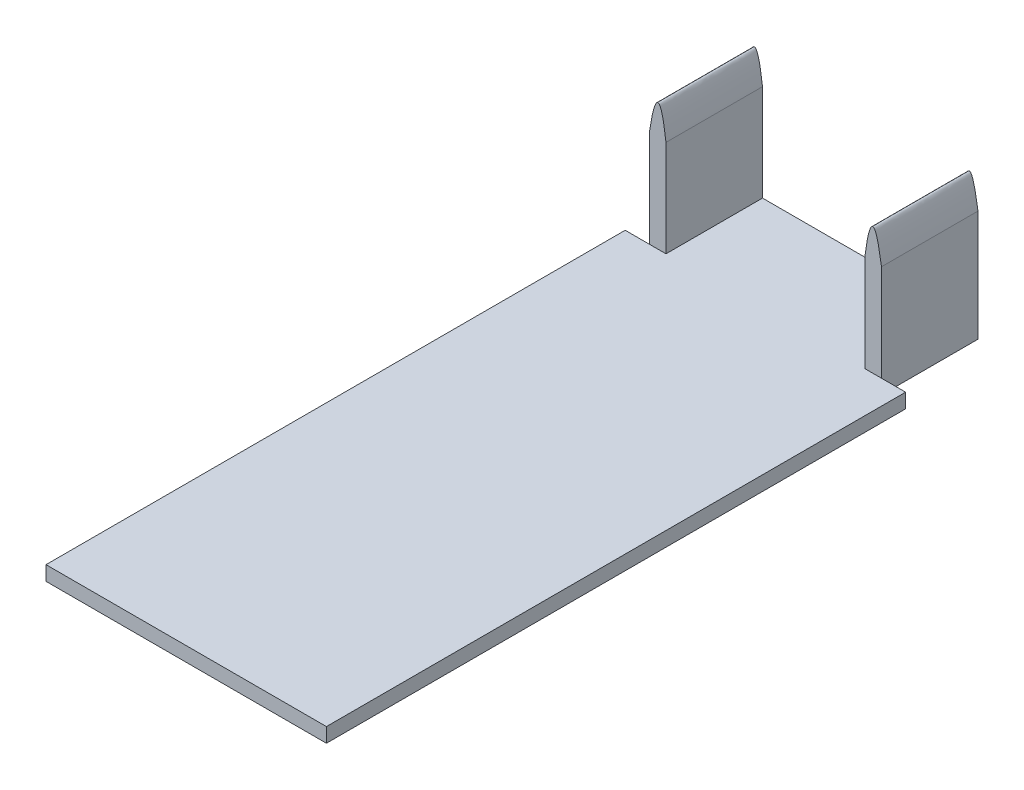
SolidWorks part; units mm, degrees
ref_plane "Front Plane" through (0, 0, 0) normal (0, 0, 1) x (1, 0, 0)
ref_plane "Top Plane" through (0, 0, 0) normal (0, 1, 0) x (1, 0, 0)
ref_plane "Right Plane" through (0, 0, 0) normal (1, 0, 0) x (0, 0, -1)
sketch "Sketch1" plane through (0, 0, 0) normal (0, 0, 1) x (1, 0, 0)
  line L0 (-31.0002, 89.8) -> (31.0002, 89.8) construction
  line L1 (-19.45, 0) -> (-19.45, 22.2)
  line L2 (-19.45, 22.2) -> (19.45, 22.2) construction
  line L3 (19.45, 3) -> (19.45, 22.2)
  line L4 (19.45, 22.2) -> (25.05, 22.2) construction
  line L5 (22.25, 22.2) -> (22.25, 16.6) construction
  line L6 (25.05, 22.2) -> (25.05, 71.1)
  line L7 (29, 72.2) -> (29, -3)
  line L8 (22.25, 16.6) -> (22.25, 71.1) construction
  line L9 (19.6329, 71.1) -> (19.6329, 64.8)
  line L10 (-22.25, 16.6) -> (-22.25, 71.1) construction
  line L11 (-22.25, 22.2) -> (-22.25, 16.6) construction
  line L12 (-19.45, 22.2) -> (-25.05, 22.2) construction
  line L13 (-19.6329, 71.1) -> (-19.5947, 64.8)
  line L14 (-29, 72.2) -> (-29, 0)
  line L15 (-25.05, 22.2) -> (-25.05, 71.1)
  line L16 (-19.45, 0) -> (-19.45, 22.2)
  line L17 (-24.05, 64.8) -> (-24.05, 41.8)
  line L18 (0, 89.8) -> (0, 69.3) construction
  line L19 (25.05, 64.8) -> (33.55, 64.8)
  line L20 (-25.05, 64.8) -> (-33.55, 64.8)
  line L21 (33.55, 64.8) -> (33.55, 61.8)
  line L22 (33.55, 61.8) -> (29, 61.8)
  line L23 (-30.35, 3) -> (29, 3)
  line L24 (-33.55, 0) -> (33.55, 0)
  line L25 (-33.55, 0) -> (-33.55, 11.2)
  line L26 (-33.55, 11.2) -> (-29, 11.2)
  line L27 (33.55, 11.2) -> (29, 11.2)
  line L28 (33.55, 0) -> (33.55, 11.2)
  line L29 (-33.55, 64.8) -> (-33.55, 61.8)
  line L30 (-33.55, 61.8) -> (-29, 61.8)
  line L31 (-24.05, 41.8) -> (24.05, 41.8)
  line L32 (-20.5947, 64.8) -> (-20.5947, 44.8)
  line L33 (-20.5947, 44.8) -> (20.5947, 44.8)
  line L34 (24.05, 64.8) -> (24.05, 41.8)
  line L35 (20.5947, 64.8) -> (20.5947, 44.8)
  arc A0 (-19.45, 22.2) -> (19.45, 22.2) centre (0, 44.8) ccw
  arc A1 (-19.5947, 64.8) -> (19.6329, 64.8) centre (0.0191, 24.3054) cw
  arc A2 (-33.55, 64.8) -> (33.55, 64.8) centre (0, 54.7879) cw
  spline S0 degree 2 poles (19.45, 22.2) (22.25, 11) (25.05, 22.2) knots 0 0 0 1 1 1
  spline S1 degree 2 poles (19.6329, 64.8) (22.1871, 77.4003) (25.05, 64.8) knots 0 0 0 1 1 1
  spline S2 degree 2 poles (-19.5947, 64.8) (-22.2005, 77.4002) (-25.05, 64.8) knots 0 0 0 1 1 1
  spline S3 degree 2 poles (-19.45, 22.2) (-22.25, 11) (-25.05, 22.2) knots 0 0 0 1 1 1
  spline S4 degree 2 poles (-25.05, 64.8) (-22.2005, 77.4002) (-19.5947, 64.8) knots 0 0 0 1 1 1
  spline S5 degree 2 poles (-24.05, 64.8) (-22.1878, 77.4001) (-20.5947, 64.8) knots 0 0 0 1 1 1
  spline S6 degree 2 poles (24.05, 64.8) (22.1878, 77.4001) (20.5947, 64.8) knots 0 0 0 1 1 1
  point P8 (0, 22.2)
  point P37 (0, 89.8)
  point P47 (-0.675, 3)
  point P50 (0, 0)
  point P56 (0, 89.8)
  point P63 (0, 41.8)
  dimension "D12" = 1
  dimension "D2" = 22.2
  dimension "D3" = 38.9
  dimension "D4" = 5.6
  dimension "D5" = 5.6
  dimension "D6" = 5.4171
  dimension "D7" = 29
  dimension "D8" = 29
  dimension "D9" = 6.3
  dimension "D10" = 0
  dimension "D11" = 6.3
  dimension "D13" = 20.5
  dimension "D14" = 8.5
  dimension "D15" = 8.5
  dimension "D16" = 89.8
  dimension "D17" = 3
  dimension "D18" = 11.2
  dimension "D19" = 3
  dimension "D20" = 1
  dimension "D21" = 20
extrude "Boss-Extrude1" add sketch "Sketch1" along normal blind 20 contours L31 L34 S6 L35 L33 L32 S5 L17
sketch "Sketch2" plane through (0, 0, 20) normal (0, 0, 1) x (1, 0, 0)
  line L0 (24.05, 64.8) -> (24.05, 41.8) construction
  line L1 (-29.05, 41.8) -> (29.05, 41.8)
  line L2 (-29.05, 41.8) -> (-29.05, 44.8)
  line L3 (-29.05, 44.8) -> (29.05, 44.8)
  line L4 (29.05, 41.8) -> (29.05, 44.8)
  line L5 (-24.05, 64.8) -> (-24.05, 41.8) construction
  line L6 (-24.05, 41.8) -> (24.05, 41.8) construction
  line L7 (-24.05, 41.8) -> (24.05, 41.8)
  point P10 (0, 41.8)
  line M6 (-24.05, 64.8) -> (-24.05, 41.8)
  line M7 (-24.05, 41.8) -> (24.05, 41.8)
  line M8 (24.05, 41.8) -> (24.05, 64.8)
  line M11 (20.5947, 44.8) -> (-20.5947, 44.8)
  dimension "D1" = 3
  dimension "D2" = 5
  dimension "D3" = 5
extrude "Boss-Extrude2" add sketch "Sketch2" along normal blind 120 contours L3 L2 L1 M6 | L3 M6 M7 M8 M11 | L1 L4 L3 M8
sketch "Sketch3" plane through (0, 0, 140) normal (0, 0, 1) x (1, 0, 0)
  line L0 (-29.05, 44.8) -> (29.05, 44.8) construction
  line L1 (-24.9, 44.8) -> (24.9, 44.8)
  line L2 (-24.9, 44.8) -> (-24.9, 41.8)
  line L3 (-24.9, 41.8) -> (24.9, 41.8)
  line L4 (24.9, 44.8) -> (24.9, 41.8)
  line L5 (-29.05, 41.8) -> (29.05, 41.8) construction
  line L6 (-29.05, 44.8) -> (29.05, 44.8)
  line L7 (-29.05, 41.8) -> (29.05, 41.8)
  line L8 (0, 44.8) -> (0, 41.8)
  point P11 (0, 0)
  point P12 (0, 41.8)
  dimension "D1" = 24.9
